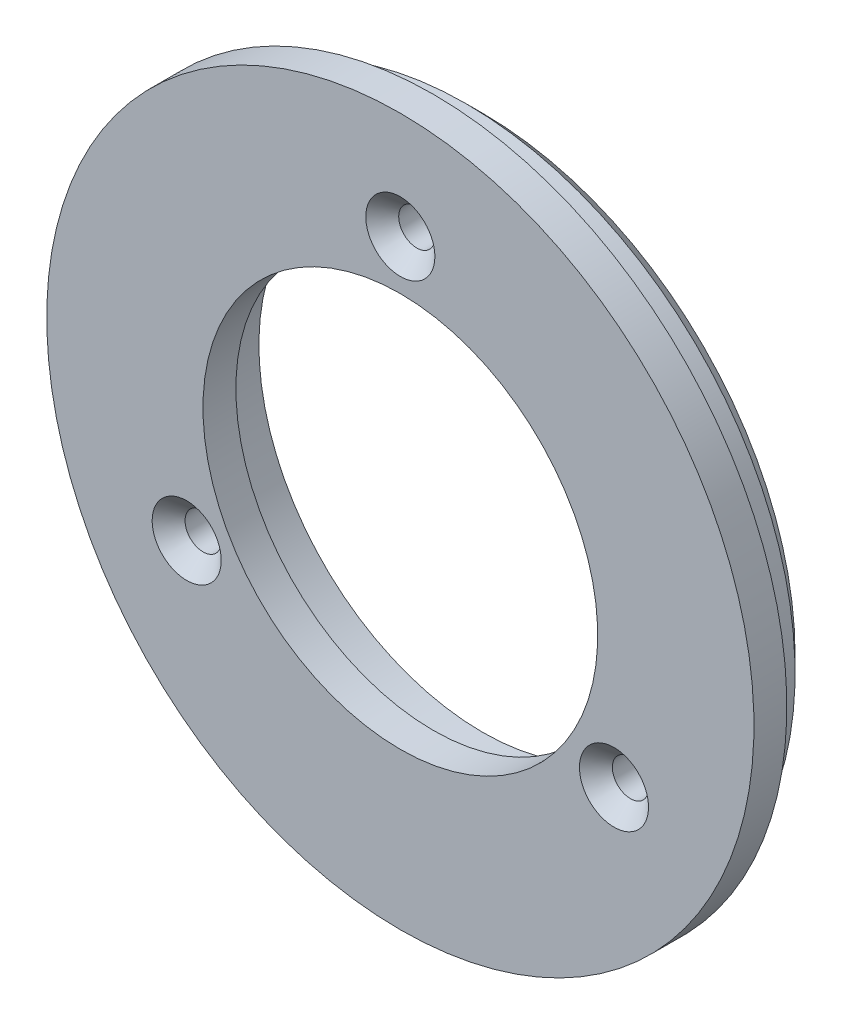
SolidWorks part; units mm, degrees
ref_plane "Front Plane" through (0, 0, 0) normal (0, 0, 1) x (1, 0, 0)
ref_plane "Top Plane" through (0, 0, 0) normal (0, 1, 0) x (1, 0, 0)
ref_plane "Right Plane" through (0, 0, 0) normal (1, 0, 0) x (0, 0, -1)
sketch "Sketch1" plane through (0, 0, 0) normal (1, 0, 0) x (0, 0, -1)
  line L0 (0, 0) -> (0, 21.5) construction
  line L1 (0, 21.5) -> (2, 21.5)
  line L2 (2, 21.5) -> (2, 20)
  line L3 (2, 20) -> (5, 20)
  line L4 (5, 20) -> (5, 13.6)
  line L5 (5, 13.6) -> (2, 13.6)
  line L6 (2, 13.6) -> (2, 0) construction
  line L8 (2, 12) -> (0, 12)
  line L9 (0, 12) -> (0, 21.5)
  line L10 (2, 12) -> (2, 13.6)
  line L11 (0, 0) -> (10.0742, 0) construction
  dimension "D1" = 21.5
  dimension "D2" = 12
  dimension "D3" = 13.6
  dimension "D4" = 20
  dimension "D5" = 2
  dimension "D6" = 5
  dimension "D7" = 2
revolve "Revolve1" add sketch "Sketch1" angle 360 about L11
chamfer "Chamfer1" distance 1 angle 45 1 edges at (0, -20, -5)
sketch "Sketch2" plane through (0, 0, -5) normal (0, 0, -1) x (-1, 0, 0)
  circle A0 centre (0, 0) radius 15 construction
  circle A1 centre (0, 15) radius 1.1
  circle A2 centre (12.9904, -7.5) radius 1.1
  circle A3 centre (-12.9904, -7.5) radius 1.1
  point P12 (0, 0)
  dimension "D1" = 30
  dimension "D2" = 2.2
  dimension "D3" = 3
extrude "Cut-Extrude1" cut sketch "Sketch2" against normal through all contours A2 | A3 | A1
chamfer "Chamfer2" distance 1 angle 45 3 edges at (-14.0904, -7.5, 0) (11.8904, -7.5, 0) (0, 16.1, 0)
